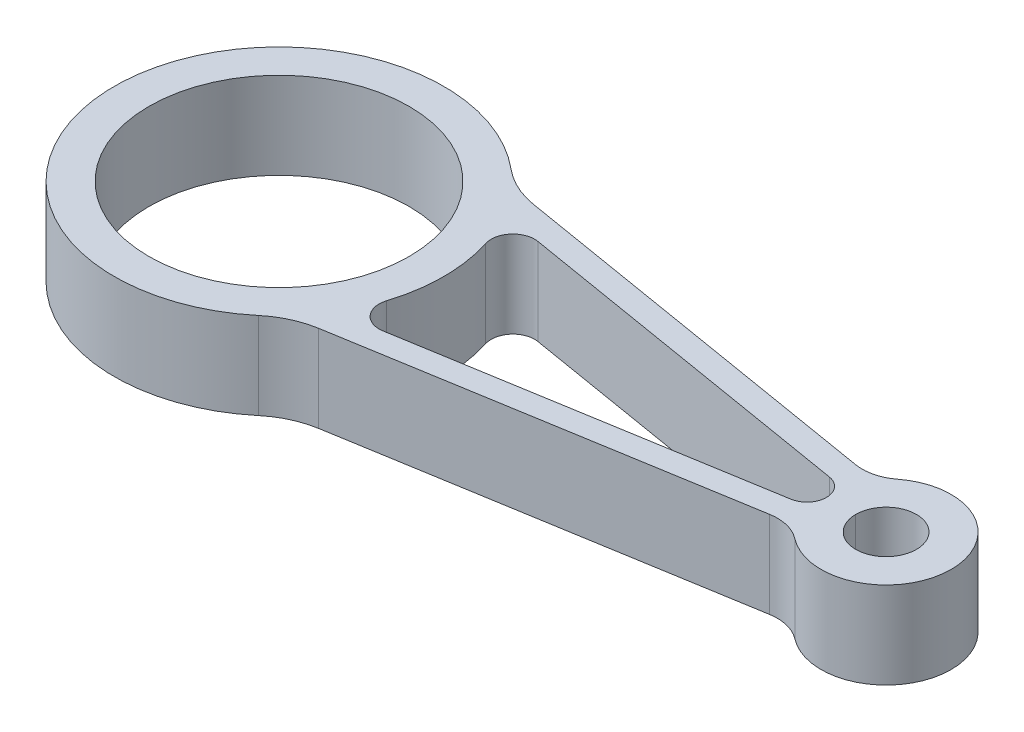
SolidWorks part; units mm, degrees
material "Plain Carbon Steel"
ref_plane "Front Plane" through (0, 0, 0) normal (0, 0, 1) x (1, 0, 0)
ref_plane "Top Plane" through (0, 0, 0) normal (0, 1, 0) x (1, 0, 0)
ref_plane "Right Plane" through (0, 0, 0) normal (1, 0, 0) x (0, 0, -1)
sketch "Sketch1" plane through (0, 0, 0) normal (0, 1, 0) x (1, 0, 0)
  line L0 (-35.0766, 0) -> (162.7337, 0) construction
  line L1 (27.9355, 25.7606) -> (128.0638, 9.0844)
  line L2 (128.0638, -9.0844) -> (27.9355, -25.7606)
  circle A0 centre (0, 0) radius 30
  circle A1 centre (140, 0) radius 7
  arc A2 (27.9355, 25.7606) -> (27.9355, -25.7606) centre (0, 0) ccw
  arc A3 (128.0638, -9.0844) -> (128.0638, 9.0844) centre (140, 0) ccw
  dimension "D1" = 60
  dimension "D2" = 14
  dimension "D4" = 76
  dimension "D5" = 30
  dimension "D3" = 140
extrude "Boss-Extrude1" add sketch "Sketch1" along normal mid plane 20 contours L0 A0 | A0 L0 | A1 L0 | L0 A1 | L2 A2 L1 A3
fillet "Fillet1" radius 10 2 edges at (128.0638, 0, 9.0844) (128.0638, 0, -9.0844)
fillet "Fillet2" radius 20 2 edges at (27.9355, 0, -25.7606) (27.9355, 0, 25.7606)
sketch "Sketch2" plane through (0, 10, 0) normal (0, 1, 0) x (1, 0, 0)
  line L0 (-14.6061, 0) -> (165.5723, 0) construction
  line L1 (41.8286, 17.871) -> (122.4784, 4.4389)
  line L2 (122.4784, -4.4389) -> (41.8286, -17.871)
  line L4 (123.0688, -9.9163) -> (33.9231, -24.7634) construction
  arc A0 (41.8286, 17.871) -> (36.2389, 11.4344) centre (41.0071, 12.9389) ccw
  arc A1 (41.8286, -17.871) -> (36.2389, -11.4344) centre (41.0071, -12.9389) cw
  arc A2 (122.4784, -4.4389) -> (122.4784, 4.4389) centre (121.7391, 0) ccw
  arc A3 (36.2389, 11.4344) -> (36.2389, -11.4344) centre (0, 0) cw
  circle A4 centre (0, 0) radius 30 construction
  dimension "D1" = 5
  dimension "D2" = 8
  dimension "D3" = 4.5
  dimension "D4" = 5.5
extrude "Cut-Extrude1" cut sketch "Sketch2" against normal blind 20
split line "Split Line2"
